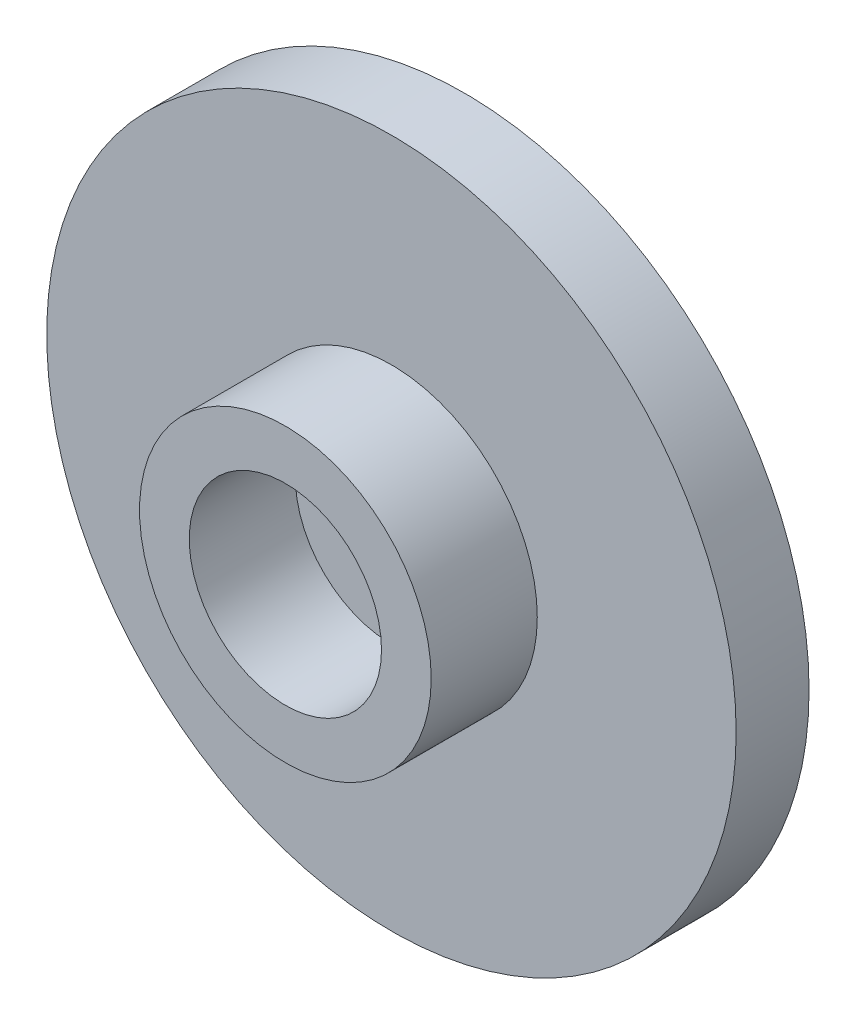
SolidWorks part; units mm, degrees
ref_plane "Front Plane" through (0, 0, 0) normal (0, 0, 1) x (1, 0, 0)
ref_plane "Top Plane" through (0, 0, 0) normal (0, 1, 0) x (1, 0, 0)
ref_plane "Right Plane" through (0, 0, 0) normal (1, 0, 0) x (0, 0, -1)
sketch "Sketch1" plane through (0, 0, 0) normal (0, 0, 1) x (1, 0, 0)
  circle A0 centre (0, 0) radius 10.4
  dimension "D1" = 20.8
extrude "Boss-Extrude1" add sketch "Sketch1" along normal blind 2.2
sketch "Sketch2" plane through (0, 0, 2.2) normal (0, 0, 1) x (1, 0, 0)
  line L0 (2.9, 0) -> (4.4, 0) construction
  circle A0 centre (0, 0) radius 4.4
  circle A1 centre (0, 0) radius 2.9
  dimension "D1" = 8.8
  dimension "D2" = 1.5
extrude "Boss-Extrude2" add sketch "Sketch2" along normal blind 3.2
